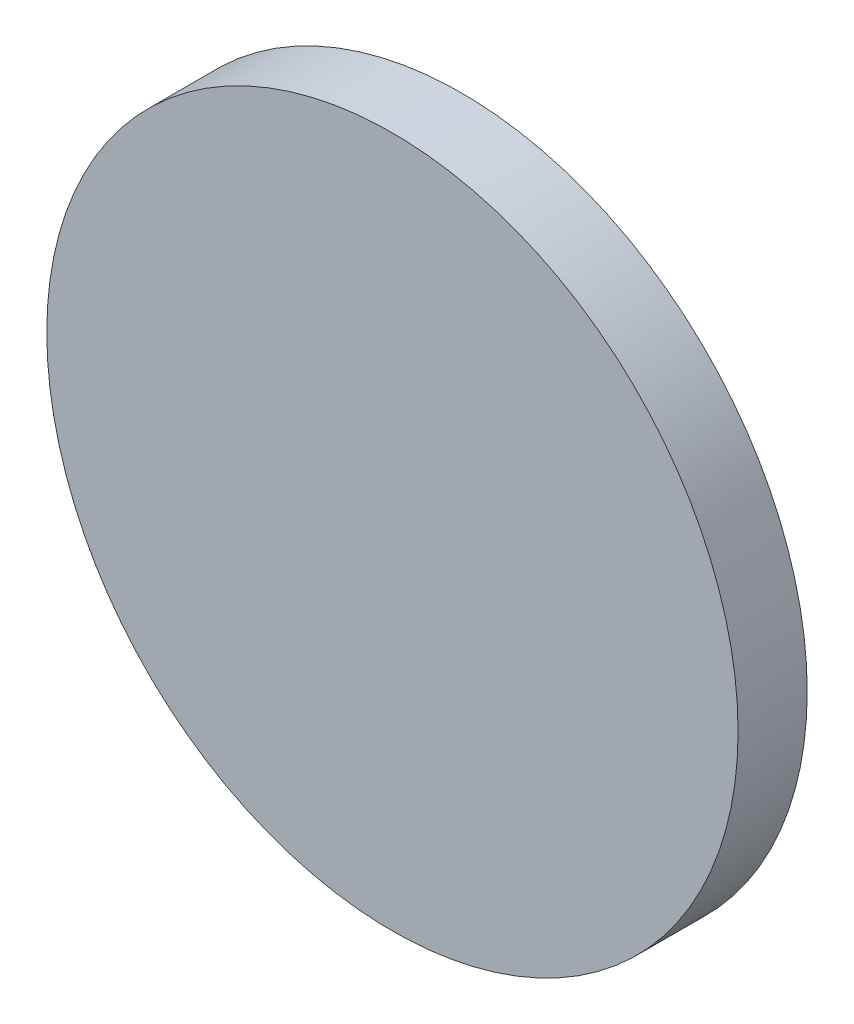
SolidWorks part; units mm, degrees
ref_plane "Plane1" through (0, 0, 0) normal (0, 0, 1) x (1, 0, 0)
ref_plane "Plane2" through (0, 0, 0) normal (0, 1, 0) x (1, 0, 0)
ref_plane "Plane3" through (0, 0, 0) normal (1, 0, 0) x (0, 0, -1)
sketch "Sketch1" plane through (0, 0, 110.55) normal (0, 0, 1) x (1, 0, 0)
  circle A0 centre (0, 0) radius 50 construction
  circle A1 centre (0, 0) radius 50
extrude "Base-Extrude" add sketch "Sketch1" against normal blind 10
